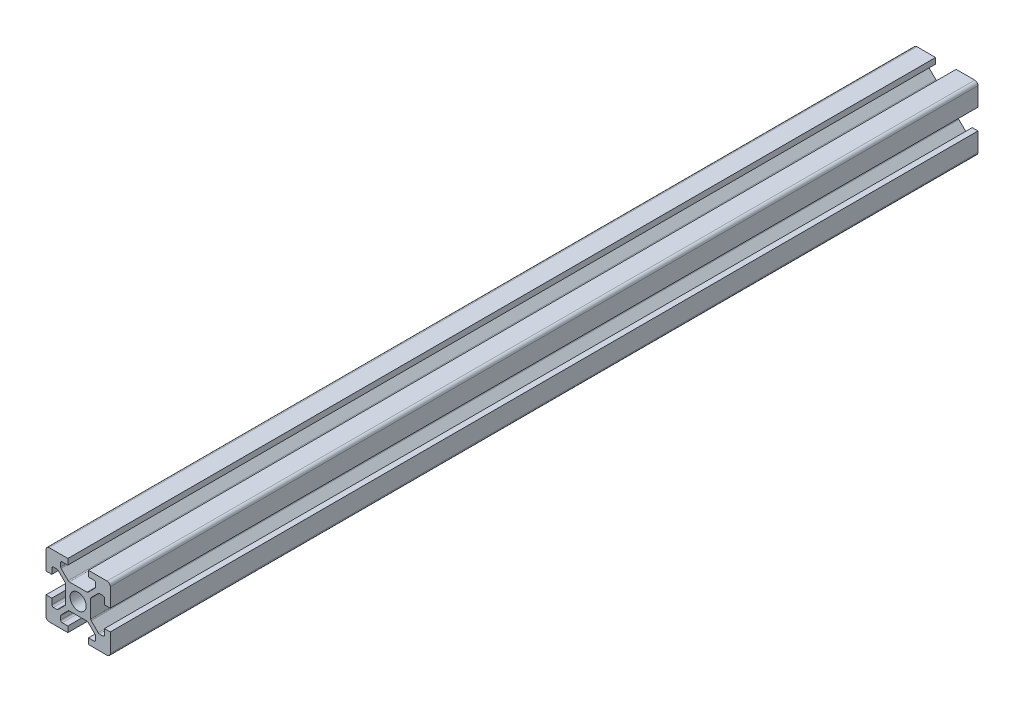
SolidWorks part; units mm, degrees
material "1060 Alloy"
ref_plane "Front Plane" through (0, 0, 0) normal (0, 0, 1) x (1, 0, 0)
ref_plane "Top Plane" through (0, 0, 0) normal (0, 1, 0) x (1, 0, 0)
ref_plane "Right Plane" through (0, 0, 0) normal (1, 0, 0) x (0, 0, -1)
sketch "Sketch1" plane through (0, 0, 0) normal (0, 0, 1) x (1, 0, 0)
  line L0 (20, 0) -> (-8.059, 28.059) construction
  line L1 (0, 0) -> (6.8, 0)
  line L2 (0, 0) -> (0, 6.8)
  line L3 (0, 20) -> (6.8, 20)
  line L4 (20, 0) -> (20, 6.8)
  line L5 (6.8, 20) -> (6.8, 18.2)
  line L6 (20, 20) -> (8.2322, 8.2322) construction
  line L7 (12.95, 6.1) -> (7.05, 6.1)
  line L8 (13.9, 7.05) -> (13.9, 12.95)
  line L9 (12.95, 13.9) -> (7.05, 13.9)
  line L10 (6.1, 7.05) -> (6.1, 12.95)
  line L11 (13.9, 6.1) -> (6.1, 13.9) construction
  line L12 (13.9, 13.9) -> (6.1, 6.1) construction
  line L13 (4.55, 16.4) -> (7.05, 13.9)
  line L14 (13.2, 18.2) -> (13.2, 20)
  line L15 (1.8, 6.8) -> (0, 6.8)
  line L16 (0, 13.2) -> (0, 20)
  line L17 (0, 13.2) -> (1.8, 13.2)
  line L18 (10, 10) -> (10, 13.9) construction
  line L19 (16.4, 4.55) -> (13.9, 7.05)
  line L20 (4.55, 16.4) -> (4.55, 18.2)
  line L21 (4.55, 18.2) -> (6.8, 18.2)
  line L22 (13.2, 18.2) -> (15.45, 18.2)
  line L23 (15.45, 18.2) -> (15.45, 16.4)
  line L24 (15.45, 16.4) -> (12.95, 13.9)
  line L25 (16.4, 4.55) -> (18.2, 4.55)
  line L26 (18.2, 4.55) -> (18.2, 6.8)
  line L27 (20, 6.8) -> (18.2, 6.8)
  line L28 (18.2, 13.2) -> (20, 13.2)
  line L29 (18.2, 13.2) -> (18.2, 15.45)
  line L30 (18.2, 15.45) -> (16.4, 15.45)
  line L31 (16.4, 15.45) -> (13.9, 12.95)
  line L32 (1.8, 4.55) -> (3.6, 4.55)
  line L33 (3.6, 15.45) -> (6.1, 12.95)
  line L34 (3.6, 15.45) -> (1.8, 15.45)
  line L35 (1.8, 15.45) -> (1.8, 13.2)
  line L36 (0, 13.2) -> (1.8, 13.2)
  line L37 (1.8, 6.8) -> (0, 6.8)
  line L38 (3.6, 4.55) -> (6.1, 7.05)
  line L39 (1.8, 6.8) -> (1.8, 4.55)
  line L40 (15.45, 3.6) -> (12.95, 6.1)
  line L41 (4.55, 3.6) -> (7.05, 6.1)
  line L42 (4.55, 1.8) -> (4.55, 3.6)
  line L43 (6.8, 1.8) -> (4.55, 1.8)
  line L44 (6.8, 1.8) -> (6.8, 0)
  line L45 (15.45, 3.6) -> (15.45, 1.8)
  line L46 (15.45, 1.8) -> (13.2, 1.8)
  line L47 (13.2, 0) -> (13.2, 1.8)
  line L48 (13.2, 20) -> (20, 20)
  line L49 (20, 13.2) -> (20, 20)
  line L50 (13.2, 0) -> (20, 0)
  line L51 (6.1, 6.1) -> (-5.5045, -5.5045) construction
  circle A0 centre (10, 10) radius 2.5
  point P25 (10, 16.4)
  point P39 (13.2, 19.1)
  point P46 (0.9, 6.8)
  dimension "D3" = 5
  dimension "D2" = 20
  dimension "D4" = 7.8
  dimension "D5" = 7.8
  dimension "D6" = 6.8
  dimension "D7" = 6.8
  dimension "D8" = 1.8
  dimension "D9" = 10.9
  dimension "D10" = 1.8
  dimension "D11" = 10.9
  dimension "D12" = 20
extrude "Boss-Extrude1" add sketch "Sketch1" along normal blind 270 contours L47 L50 L4 L27 L26 L25 L19 L8 L31 L30 L29 L28 L49 L48 L14 L22 L23 L24 L9 L13 L20 L21 L5 L3 L16 L17 L35 L34 L33 L10 L38 L32 L39 L15 L2 L1 L44 L43 L42 L41 L7 L40 L45 L46 A0
fillet "Fillet1" radius 1 4 edges at (20, 20, 135) (20, 0, 135) (0, 0, 135) (0, 20, 135)
fillet "Fillet2" radius 0.5 6 edges at (4.55, 18.2, 135) (4.55, 16.4, 135) (7.05, 13.9, 135) (15.45, 18.2, 135) (15.45, 16.4, 135) (12.95, 13.9, 135)
fillet "Fillet3" radius 0.5 6 edges at (18.2, 15.45, 135) (16.4, 15.45, 135) (13.9, 12.95, 135) (18.2, 4.55, 135) (13.9, 7.05, 135) (16.4, 4.55, 135)
fillet "Fillet4" radius 0.5 6 edges at (1.8, 15.45, 135) (3.6, 15.45, 135) (6.1, 12.95, 135) (3.6, 4.55, 135) (1.8, 4.55, 135) (6.1, 7.05, 135)
fillet "Fillet5" radius 0.5 6 edges at (7.05, 6.1, 135) (4.55, 3.6, 135) (4.55, 1.8, 135) (15.45, 1.8, 135) (15.45, 3.6, 135) (12.95, 6.1, 135)
